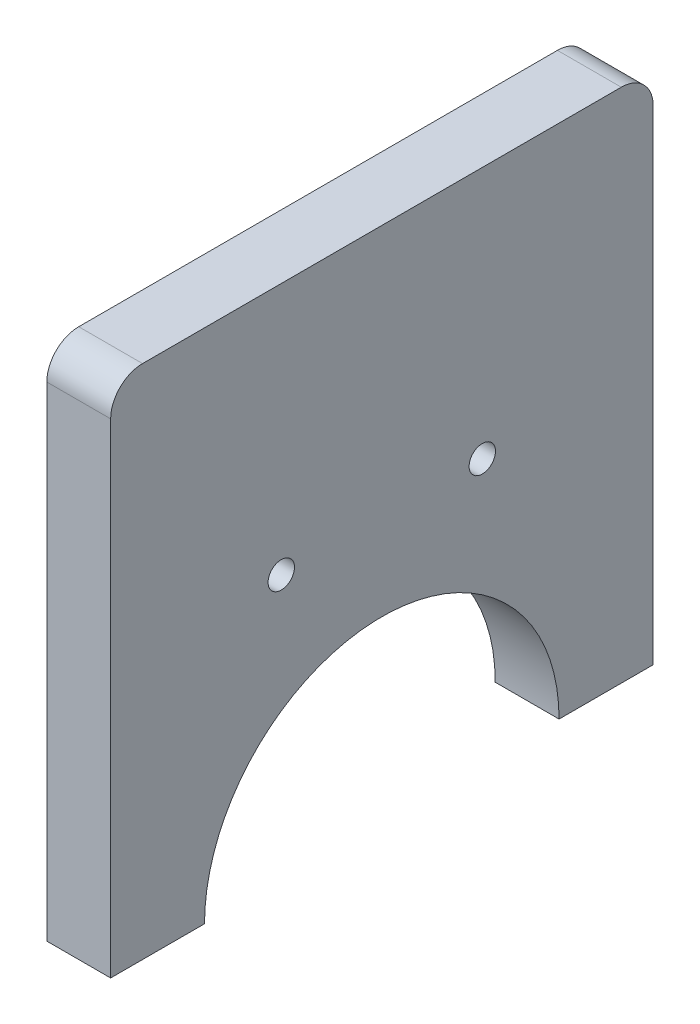
SolidWorks part; units mm, degrees
material "ABS"
ref_plane "Front Plane" through (0, 0, 0) normal (0, 0, 1) x (1, 0, 0)
ref_plane "Top Plane" through (0, 0, 0) normal (0, 1, 0) x (1, 0, 0)
ref_plane "Right Plane" through (0, 0, 0) normal (1, 0, 0) x (0, 0, -1)
sketch "Sketch1" plane through (0, 0, 58.7304) normal (0, 0, 1) x (1, 0, 0)
  line L0 (-14.2137, 28.5958) -> (-14.2137, 47.5958)
  line L1 (36.7863, 47.5958) -> (-14.2137, 47.5958)
  line L2 (33.7863, 47.5958) -> (-11.2137, 47.5958) construction
  line L3 (-14.2137, 28.5958) -> (-19.2937, 28.5958)
  line L4 (-19.2937, 28.5958) -> (-19.2937, 52.6758)
  line L5 (-19.2937, 52.6758) -> (41.8663, 52.6758)
  line L6 (11.2863, 20.8439) -> (11.2863, 64.7229) construction
  line L7 (36.7863, 28.5958) -> (36.7863, 47.5958)
  line L8 (36.7863, 28.5958) -> (41.8663, 28.5958)
  line L9 (41.8663, 28.5958) -> (41.8663, 52.6758)
  point P12 (11.2863, 52.6758)
  point P13 (11.2863, 47.5958)
  dimension "D1" = 5.08
  dimension "D2" = 5.08
extrude "Boss-Extrude1" add sketch "Sketch1" against normal blind 43.18 from offset 5.08
sketch "Sketch2" plane through (0, 0, 20.6304) normal (0, 0, -1) x (-1, 0, 0)
  line L0 (-36.7863, 39.3638) -> (14.2137, 39.3638)
  line L1 (-36.7863, 47.5958) -> (-36.7863, 28.5958) construction
  line L2 (14.2137, 28.5958) -> (14.2137, 47.5958) construction
  line L3 (14.2137, 39.3638) -> (14.2137, 47.5958)
  line L4 (14.2137, 47.5958) -> (-36.7863, 47.5958)
  line L5 (-36.7863, 47.5958) -> (-36.7863, 39.3638)
extrude "Boss-Extrude2" add sketch "Sketch2" against normal blind 5.08
sketch "Sketch3" plane through (36.7863, 0, 0) normal (-1, 0, 0) x (0, 0, 1)
  circle A0 centre (50.2304, 32.5958) radius 1.05
  circle A1 centre (34.2304, 32.5958) radius 1.05
extrude "Cut-Extrude1" cut sketch "Sketch3" against normal blind 5.08 and the other way through all
sketch "Sketch4" plane through (0, 47.5958, 0) normal (0, -1, 0) x (-1, 0, 0)
  circle A0 centre (-22.2863, -42.2304) radius 1.25
  circle A1 centre (-11.2863, -53.2304) radius 1.25
  circle A2 centre (-11.2863, -31.2304) radius 1.25
  circle A3 centre (-0.2863, -42.2304) radius 1.25
extrude "Cut-Extrude2" cut sketch "Sketch4" against normal blind 5.08
sketch "Sketch5" plane through (0, 0, 63.8104) normal (0, 0, 1) x (1, 0, 0)
  line L0 (-14.2137, 39.3638) -> (36.7863, 39.3638)
  line L1 (36.7863, 39.3638) -> (36.7863, 47.5958)
  line L2 (36.7863, 47.5958) -> (-14.2137, 47.5958)
  line L3 (-14.2137, 47.5958) -> (-14.2137, 39.3638)
extrude "Boss-Extrude3" add sketch "Sketch5" against normal blind 5.08
sketch "Sketch6" plane through (-19.2937, 0, 0) normal (-1, 0, 0) x (0, 0, 1)
  line L0 (20.6304, 28.5958) -> (20.6304, 11.5958)
  line L1 (20.6304, 11.5958) -> (28.1208, 11.5958)
  line L2 (56.34, 11.5958) -> (72.2607, 11.5958)
  line L3 (63.8104, 28.5958) -> (63.8104, 11.5958)
  line L4 (63.8104, 28.5958) -> (20.6304, 28.5958)
  arc A0 (56.34, 11.5958) -> (28.1208, 11.5958) centre (42.2304, 11.5958) ccw
  line M5 (20.6304, 28.5958) -> (63.8104, 28.5958)
extrude "Boss-Extrude4" add sketch "Sketch6" against normal blind 5.08 contours A0 L2 L3 L0 L1 M5
fillet "Fillet1" radius 2.54 7 edges at (39.3263, 28.5958, 20.6304) (39.3263, 28.5958, 63.8104) (-14.2137, 39.3638, 23.1704) (-14.2137, 39.3638, 61.2704) (11.2863, 52.6758, 63.8104) (41.8663, 52.6758, 42.2204) (11.2863, 52.6758, 20.6304)
sketch "Sketch7" plane through (0, 0, 63.8104) normal (0, 0, 1) x (1, 0, 0)
  line L0 (-14.2137, 11.5958) -> (-14.2137, 36.8238) construction
  line L1 (-14.2137, 18.4396) -> (60.989, 18.4396)
  line L2 (-14.2137, 18.4396) -> (-14.2137, 60.0996)
  line L3 (-14.2137, 60.0996) -> (60.989, 60.0996)
  line L4 (60.989, 18.4396) -> (60.989, 60.0996)
extrude "Cut-Extrude3" cut sketch "Sketch7" against normal through all
